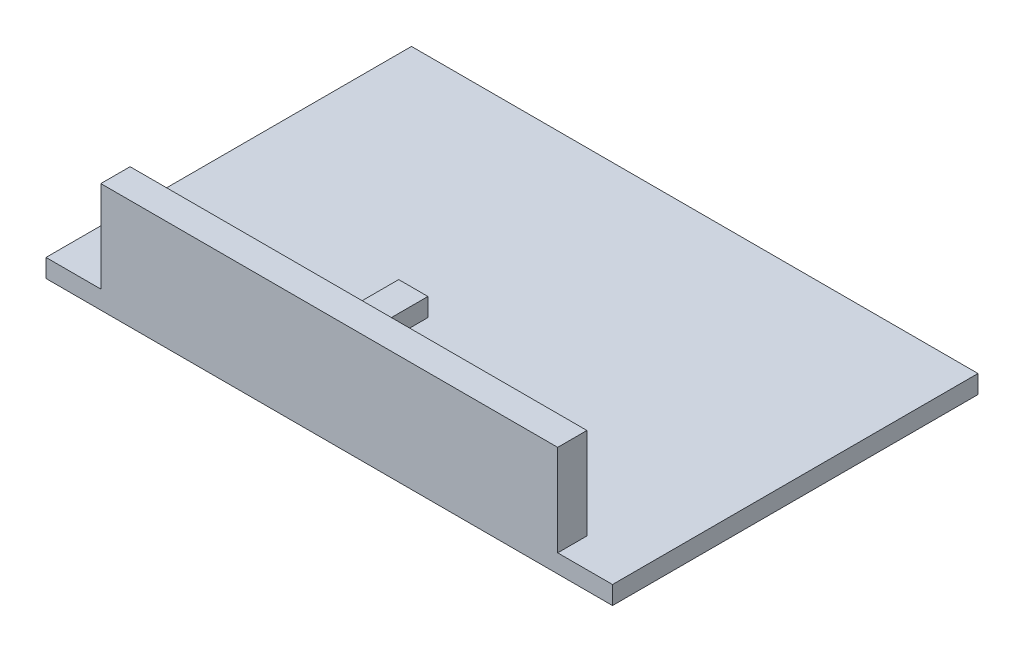
SolidWorks part; units mm, degrees
ref_plane "前视基准面" through (0, 0, 0) normal (0, 0, 1) x (1, 0, 0)
ref_plane "上视基准面" through (0, 0, 0) normal (0, 1, 0) x (1, 0, 0)
ref_plane "右视基准面" through (0, 0, 0) normal (1, 0, 0) x (0, 0, -1)
sketch "草图1" plane through (0, 0, 0) normal (0, 1, 0) x (1, 0, 0)
  line L1 (0, 0) -> (155, 0)
  line L2 (0, 0) -> (0, 100)
  line L3 (0, 100) -> (155, 100)
  line L4 (155, 0) -> (155, 100)
  dimension "D1" = 155
  dimension "D2" = 100
extrude "凸台-拉伸1" add sketch "草图1" along normal blind 5
sketch "草图2" plane through (0, 5, 0) normal (0, 1, 0) x (1, 0, 0)
  line L0 (0, 0) -> (155, 0) construction
  line L1 (15, 0) -> (140, 0)
  line L2 (15, 0) -> (15, 8)
  line L3 (15, 8) -> (140, 8)
  line L4 (140, 0) -> (140, 8)
  line L5 (0, 100) -> (0, 0) construction
  line L6 (155, 0) -> (155, 100) construction
  dimension "D1" = 15
  dimension "D2" = 15
  dimension "D3" = 8
extrude "凸台-拉伸2" add sketch "草图2" along normal blind 25
sketch "草图3" plane through (0, 0, -8) normal (0, 0, -1) x (-1, 0, 0)
  line L0 (-77.5, 30) -> (-77.5, 5) construction
  line L3 (-62, 30) -> (-62, 5) construction
  line L4 (-50.5, 30) -> (-50.5, 5) construction
  line L5 (-39.5, 30) -> (-39.5, 5) construction
  line L6 (-37.5, 30) -> (-37.5, 5) construction
  dimension "D1" = 15.5
  dimension "D2" = 27
  dimension "D3" = 38
  dimension "D4" = 40
sketch3d "3D草图2"
  line L0 (77.5, 30, -8) -> (77.5, 5, -8) construction
  line L1 (62, 30, -8) -> (62, 5, -8) construction
  line L2 (50.5, 30, -8) -> (50.5, 5, -8) construction
  line L3 (39.5, 30, -8) -> (39.5, 5, -8) construction
  line L4 (37.5, 30, -8) -> (37.5, 5, -8) construction
sketch "草图4" plane through (0, 0, -8) normal (0, 0, -1) x (-1, 0, 0)
  line L0 (-140, 25) -> (-15, 25) construction
  line L3 (-140, 5) -> (-15, 5) construction
  dimension "D1" = 20
sketch "草图7" plane through (0, 0, -8) normal (0, 0, -1) x (-1, 0, 0)
  line L0 (-140, 25) -> (-15, 25) construction
  line L1 (-81.5, 25) -> (-73.5, 25)
  line L2 (-81.5, 25) -> (-81.5, 20)
  line L3 (-81.5, 20) -> (-73.5, 20)
  line L4 (-73.5, 25) -> (-73.5, 20)
  line L5 (-77.5, 200030) -> (-77.5, -199995) construction
  dimension "D1" = 4
  dimension "D2" = 8
  dimension "D3" = 5
extrude "凸台-拉伸3" add sketch "草图7" along normal blind 15
